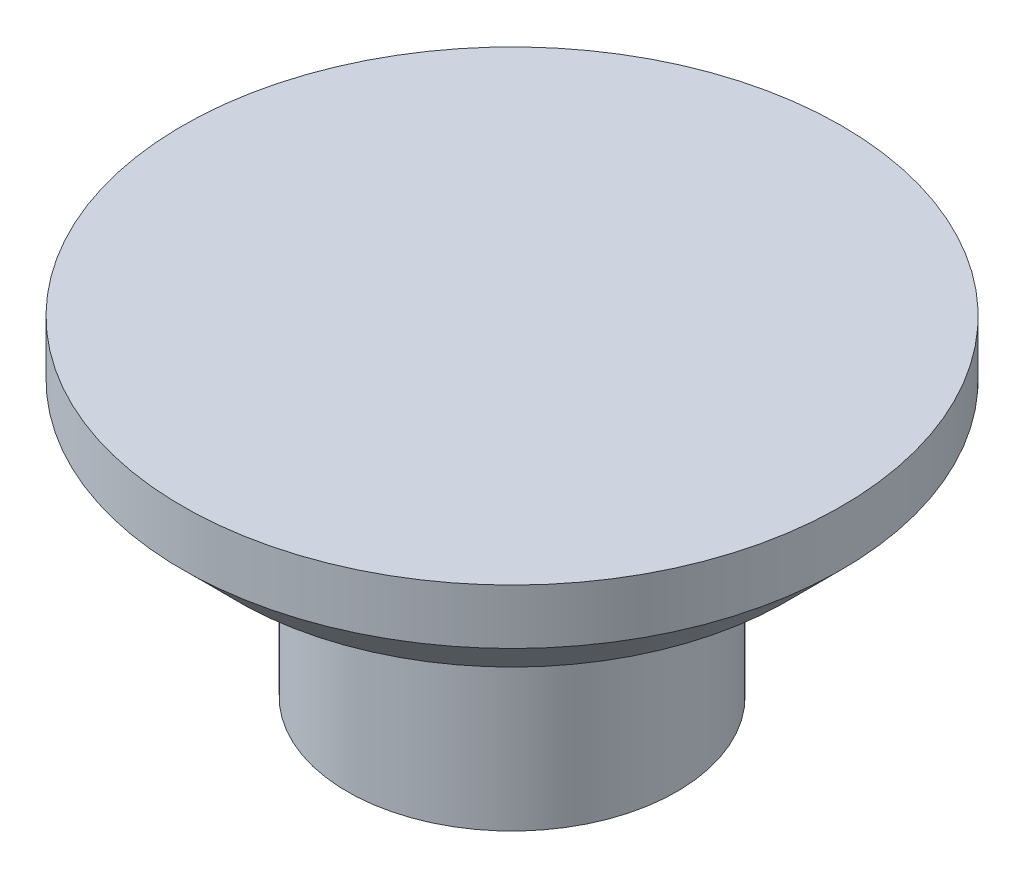
SolidWorks part; units mm, degrees
ref_plane "Płaszczyzna przednia" through (0, 0, 0) normal (0, 0, 1) x (1, 0, 0)
ref_plane "Płaszczyzna górna" through (0, 0, 0) normal (0, 1, 0) x (1, 0, 0)
ref_plane "Płaszczyzna prawa" through (0, 0, 0) normal (1, 0, 0) x (0, 0, -1)
sketch "Szkic1" plane through (0, 0, 0) normal (0, 0, 1) x (1, 0, 0)
  line L0 (0, 0) -> (6, 0)
  line L1 (6, 0) -> (6, -1)
  line L2 (5, -2) -> (4, -2)
  line L3 (3, -3) -> (3, -6)
  line L4 (3, -6) -> (1.5, -6)
  line L5 (0, -4.5) -> (0, 0)
  line L6 (6, -1) -> (5, -2)
  arc A0 (1.5, -6) -> (0, -4.5) centre (0, -6) ccw
  arc A1 (4, -2) -> (3, -3) centre (4, -3) ccw
  point P4 (6, -2)
  point P11 (3, -2)
  dimension "D5" = 3
  dimension "D6" = 1
  dimension "D1" = 6
  dimension "D2" = 2
  dimension "D3" = 3
  dimension "D4" = 6
revolve "Obrót1" add sketch "Szkic1" angle 360 about L5
